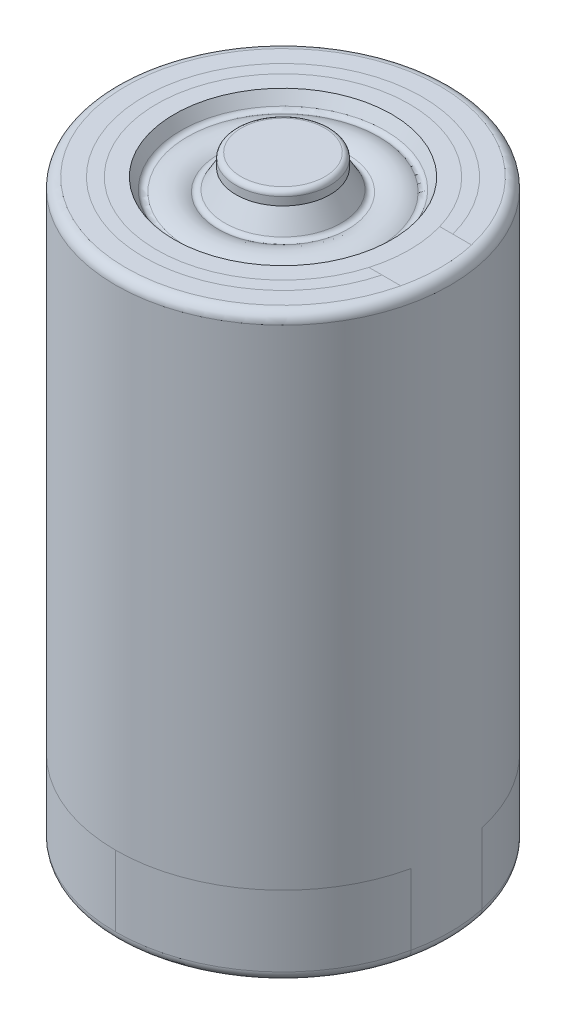
SolidWorks part; units mm, degrees
ref_plane "Front Plane" through (0, 0, 0) normal (0, 0, 1) x (1, 0, 0)
ref_plane "Top Plane" through (0, 0, 0) normal (0, 1, 0) x (1, 0, 0)
ref_plane "Right Plane" through (0, 0, 0) normal (1, 0, 0) x (0, 0, -1)
sketch "Sketch2" plane through (0, 0, 0) normal (0, 0, 1) x (1, 0, 0)
  line L0 (0, 0) -> (0, 66.982) construction
  line L1 (0, 0) -> (9, 0)
  line L2 (9, 0) -> (9.866, 0.5)
  line L3 (9.866, 0.5) -> (11.5, 0.5)
  line L4 (12.5, 1.5) -> (15.55, 1.5)
  line L5 (16.55, 2.5) -> (16.55, 57.9)
  line L6 (15.55, 58.9) -> (10.75, 58.9)
  line L7 (10.75, 58.9) -> (10.1215, 57.8113)
  line L8 (5.7404, 57.8113) -> (4.65, 59.7)
  line L9 (4.65, 59.7) -> (4.65, 60.5)
  line L10 (4.15, 61) -> (0, 61)
  line L11 (0, 61) -> (0, 0)
  line L12 (4.2439, 58) -> (10.8907, 58) construction
  arc A0 (11.5, 0.5) -> (12.5, 1.5) centre (11.5, 1.5) ccw
  arc A1 (15.55, 1.5) -> (16.55, 2.5) centre (15.55, 2.5) ccw
  arc A2 (16.55, 57.9) -> (15.55, 58.9) centre (15.55, 57.9) ccw
  arc A3 (6.4084, 57.62) -> (9.4535, 57.62) centre (7.9309, 54.7601) cw
  arc A4 (4.65, 60.5) -> (4.15, 61) centre (4.15, 60.5) ccw
  arc A5 (10.1215, 57.8113) -> (9.4535, 57.62) centre (9.6884, 58.0613) cw
  arc A6 (6.4084, 57.62) -> (5.7404, 57.8113) centre (6.1734, 58.0613) cw
  point P27 (9.8619, 57.3617)
  point P30 (6, 57.3617)
  dimension "D7" = 1
  dimension "D11" = 1
  dimension "D16" = 0.5
  dimension "D19" = 0.5
  dimension "D1" = 18
  dimension "D2" = 0.5
  dimension "D3" = 30
  dimension "D4" = 25
  dimension "D5" = 1
  dimension "D6" = 33.1
  dimension "D8" = 9.3
  dimension "D9" = 1.3
  dimension "D10" = 2.1
  dimension "D12" = 61
  dimension "D13" = 12
  dimension "D14" = 3
  dimension "D15" = 21.5
  dimension "D17" = 30
  dimension "D18" = 60
revolve "Revolve1" add sketch "Sketch2" angle 360 about L0
sketch "Sketch3" plane through (0, 58.9, 0) normal (0, 1, 0) x (1, 0, 0)
  circle A0 centre (0, 0) radius 12.5
  dimension "D1" = 25
split line "Split Line1"
sketch "Sketch5" plane through (0, 0, 0) normal (1, 0, 0) x (0, 0, -1)
  line L1 (-3.5, 9.5) -> (-16.55, 9.5)
  line L2 (-3.5, 9.5) -> (-3.5, 0)
  line L3 (-3.5, 0) -> (3.5, 0)
  line L4 (3.5, 9.5) -> (3.5, 0)
  line L5 (-9, 0) -> (9, 0) construction
  line L7 (-16.55, 9.5) -> (-16.55, -1)
  line L8 (-16.55, -1) -> (16.55, -1)
  line L9 (16.55, -1) -> (16.55, 9.5)
  line L10 (16.55, 9.5) -> (3.5, 9.5)
  line L11 (-15.55, 1.5) -> (15.55, 1.5) construction
  line L12 (-16.55, 57.9) -> (-16.55, 2.5) construction
  line L13 (16.55, 2.5) -> (16.55, 57.9) construction
  dimension "D1" = 3.5
  dimension "D2" = 7
  dimension "D3" = 8
  dimension "D4" = 1
split line "Split Line4"
sketch "Sketch6" plane through (0, 0, 0) normal (1, 0, 0) x (0, 0, -1)
  line L0 (16.55, 9.5) -> (3.5, 9.5) construction
  line L1 (16.55, 9.5) -> (-16.55, 9.5)
  line L2 (-16.55, 57.9) -> (-16.55, 9.5) construction
split line "Split Line5"
sketch "Sketch7" plane through (0, 58.9, 0) normal (0, 1, 0) x (1, 0, 0)
  line L0 (20.9118, -3.5) -> (10.5743, -3.5)
  line L1 (10.9976, 3.5) -> (19.728, 3.5)
split line "Split Line6"
sketch "Sketch8" plane through (0, 58.9, 0) normal (0, 1, 0) x (1, 0, 0)
  line L0 (15.151, 3.5) -> (12, 3.5) construction
  line L1 (12, -3.5) -> (15.151, -3.5) construction
  line L2 (13.2971, 3.5) -> (12, 3.5)
  line L3 (12, -3.5) -> (13.2971, -3.5)
  arc A0 (13.2971, 3.5) -> (13.2971, -3.5) centre (0, 0) ccw
  dimension "D1" = 27.5
split line "Split Line9"
